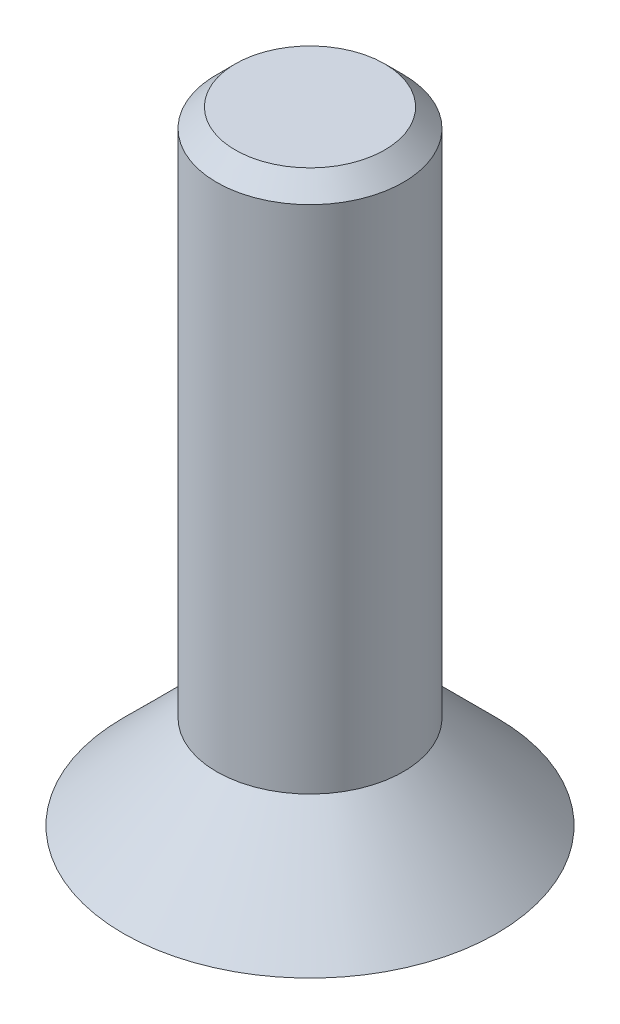
SolidWorks part; units mm, degrees
ref_plane "前视基准面" through (0, 0, 0) normal (0, 0, 1) x (1, 0, 0)
ref_plane "上视基准面" through (0, 0, 0) normal (0, 1, 0) x (1, 0, 0)
ref_plane "右视基准面" through (0, 0, 0) normal (1, 0, 0) x (0, 0, -1)
other "Configuration Table"
sketch "轴向轮廓" plane through (0, 0, 0) normal (0, 0, 1) x (1, 0, 0)
  line L0 (0, 0) -> (3, 0)
  line L1 (3, 0) -> (1.5, 1.5)
  line L2 (1.5, 1.5) -> (1.5, 9.7)
  line L3 (1.5, 9.7) -> (1.2, 10)
  line L4 (1.2, 10) -> (0, 10)
  line L5 (0, 10) -> (0, 0)
  line L6 (0, -2) -> (0, 12) construction
revolve "螺钉外形_旋转" add sketch "轴向轮廓" angle 360 about L6
sketch "内六角轮廓" plane through (0, 0, 0) normal (0, -1, 0) x (1, 0, 0)
  line L0 (1.1547, 0) -> (0.5774, 1)
  line L1 (0.5774, 1) -> (-0.5774, 1)
  line L2 (-0.5774, 1) -> (-1.1547, 0)
  line L3 (-1.1547, 0) -> (-0.5774, -1)
  line L4 (-0.5774, -1) -> (0.5774, -1)
  line L5 (0.5774, -1) -> (1.1547, 0)
extrude "内六角" cut sketch "内六角轮廓" against normal blind 1.1
